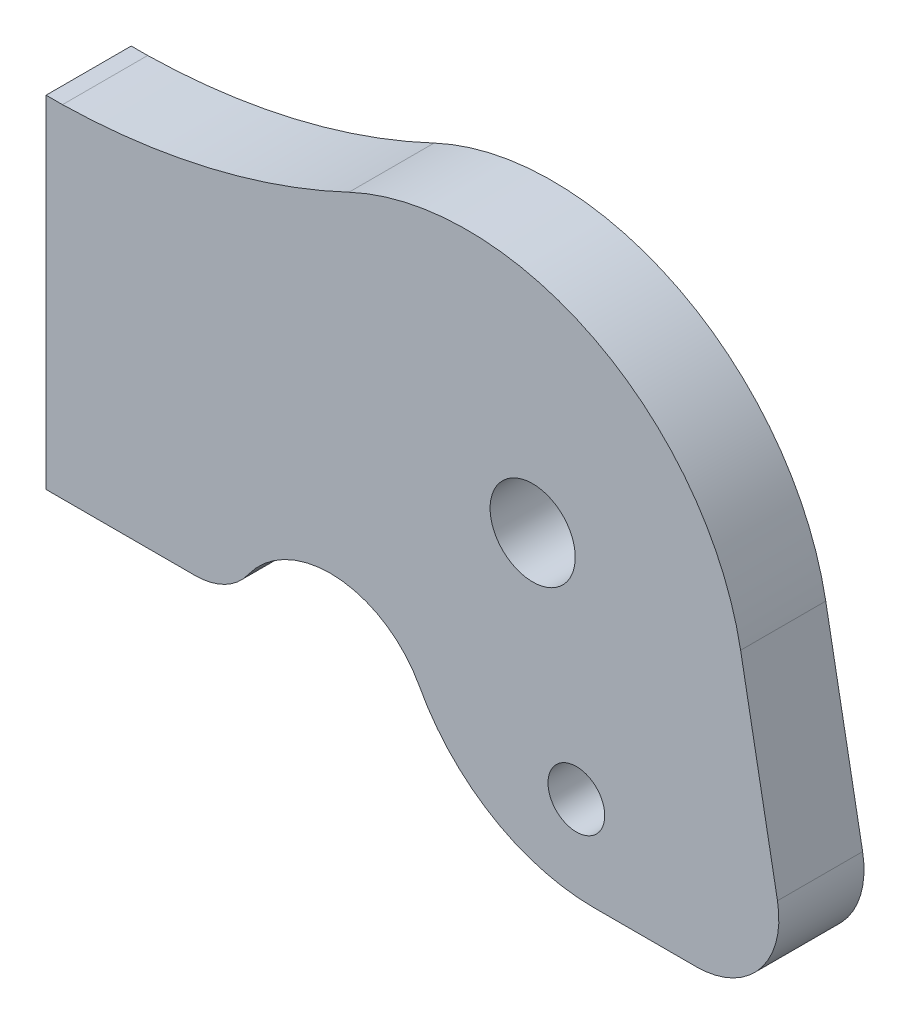
SolidWorks part; units mm, degrees
ref_plane "Front" through (0, 0, 0) normal (0, 0, 1) x (1, 0, 0)
ref_plane "Top" through (0, 0, 0) normal (0, 1, 0) x (1, 0, 0)
ref_plane "Right" through (0, 0, 0) normal (1, 0, 0) x (0, 0, -1)
sketch "Sketch1" plane through (0, 0, 0) normal (0, 0, 1) x (1, 0, 0)
  line L0 (5.57, 2.0207) -> (6.8692, -4.974)
  line L5 (4.005, -8.4191) -> (0.4105, -8.4191)
  line L6 (-13.6514, -5.3099) -> (-18.9009, -5.3099)
  line L7 (-18.9009, -5.3099) -> (-18.9009, 6.723)
  line L8 (-18.9009, 6.723) -> (-18.3219, 6.723)
  circle A0 centre (-1.7567, 1.9409) radius 1.5
  circle A1 centre (-0.2167, -5.4191) radius 1
  arc A2 (-8.264, 9.0809) -> (5.57, 2.0207) centre (-4.0615, 0.2318) cw
  arc A3 (6.8692, -4.974) -> (4.005, -8.4191) centre (4.005, -5.506) cw
  arc A4 (0.4105, -8.4191) -> (-5.7491, -4.7344) centre (0.4105, -1.4284) cw
  arc A5 (-11.7827, -4.3484) -> (-5.7491, -4.7344) centre (-8.886, -6.418) cw
  arc A6 (-11.7827, -4.3484) -> (-13.6514, -5.3099) centre (-13.6514, -3.0133) cw
  arc A7 (-18.3219, 6.723) -> (-8.2307, 9.0967) centre (-18.8117, 31.4424) ccw
  dimension "D1" = 3
  dimension "D2" = 2
  dimension "D9" = 2
  dimension "D3" = 7.36
extrude "Boss-Extrude1" add sketch "Sketch1" along normal blind 3 contours A7 L8 L7 L6 A6 A5 A4 L5 A3 L0 A2 A1 A0
